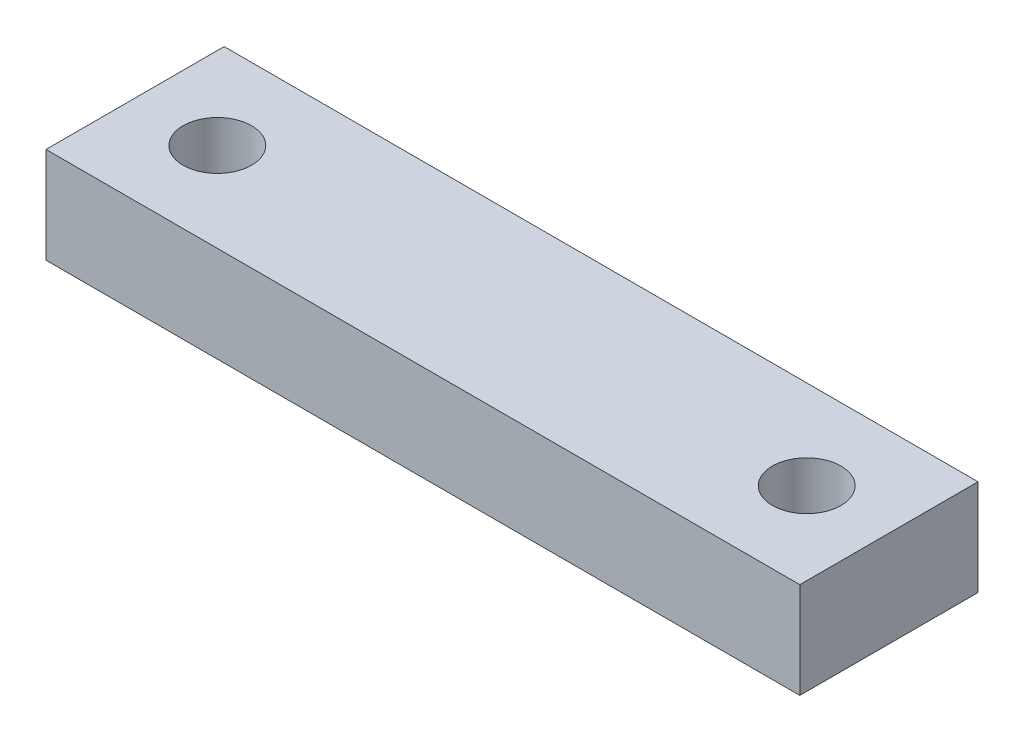
SolidWorks part; units mm, degrees
ref_plane "Front Plane" through (0, 0, 0) normal (0, 0, 1) x (1, 0, 0)
ref_plane "Top Plane" through (0, 0, 0) normal (0, 1, 0) x (1, 0, 0)
ref_plane "Right Plane" through (0, 0, 0) normal (1, 0, 0) x (0, 0, -1)
sketch "Sketch1" plane through (0, 0, 0) normal (0, 1, 0) x (1, 0, 0)
  line L1 (-27.5, 6.5) -> (27.5, 6.5)
  line L2 (-27.5, 6.5) -> (-27.5, -6.5)
  line L3 (-27.5, -6.5) -> (27.5, -6.5)
  line L4 (27.5, 6.5) -> (27.5, -6.5)
  line L5 (-27.5, 6.5) -> (27.5, -6.5) construction
  line L6 (-27.5, -6.5) -> (27.5, 6.5) construction
  point P0 (0, 0)
  dimension "D1" = 55
  dimension "D2" = 13
extrude "Boss-Extrude1" add sketch "Sketch1" along normal blind 7
sketch "Sketch2" plane through (0, 7, 0) normal (0, 1, 0) x (1, 0, 0)
  line L0 (-27.5, 0) -> (-21.5, 0) construction
  line L1 (-27.5, 6.5) -> (-27.5, -6.5) construction
  line L2 (0, 6.5) -> (0, -6.5) construction
  line L3 (27.5, 6.5) -> (-27.5, 6.5) construction
  line L4 (-27.5, -6.5) -> (27.5, -6.5) construction
  circle A0 centre (-21.5, 0) radius 2.5
  circle A1 centre (21.5, 0) radius 2.5
  dimension "D2" = 5
  dimension "D1" = 6
extrude "Cut-Extrude1" cut sketch "Sketch2" against normal blind 7
